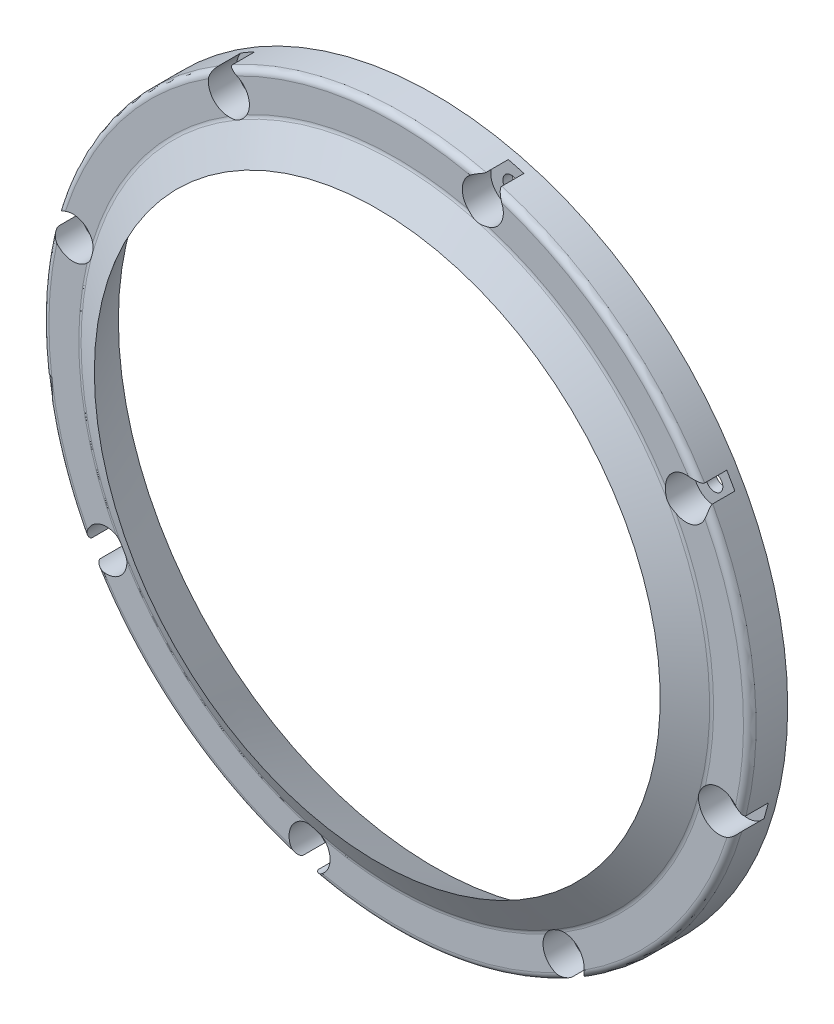
SolidWorks part; units mm, degrees
material "PUR"
ref_plane "Front Plane" through (0, 0, 0) normal (0, 0, 1) x (1, 0, 0)
ref_plane "Top Plane" through (0, 0, 0) normal (0, 1, 0) x (1, 0, 0)
ref_plane "Right Plane" through (0, 0, 0) normal (1, 0, 0) x (0, 0, -1)
sketch "Sketch1" plane through (0, 0, 0) normal (0, 0, 1) x (1, 0, 0)
  circle A0 centre (0, 0) radius 100 construction
  circle A1 centre (0, 0) radius 100
  circle A2 centre (0, 0) radius 112
  arc A3 (111.914, 4.3889) -> (-77.2845, 81.0624) centre (0, 0) ccw construction
sketch "Sketch2" plane through (0, 0, 0) normal (0, 1, 0) x (1, 0, 0)
  line L0 (-112, 0) -> (112, 0) construction
  line L1 (-100, 0) -> (100, 0) construction
  line L2 (-112, 0) -> (112, 0) construction
  line L3 (-100, 0) -> (100, 0) construction
  line L4 (-100, 0) -> (-112, 0)
  line L5 (-100, 0) -> (-89.6077, -18)
  line L6 (0, 0) -> (0, -18) construction
  line L7 (-112, 0) -> (-112, -12)
  line L8 (-89.6077, -18) -> (0, -18) construction
  line L9 (-89.6077, -18) -> (-100, -12)
  line L10 (-100, -12) -> (-112, -12)
  line L11 (-100, -12) -> (-100, 0) construction
  dimension "D1" = 60
  dimension "D2" = 12
  dimension "D3" = 18
revolve "Revolve1" add sketch "Sketch2" angle 360 about L6
fillet "Fillet1" radius 2 2 edges at (-112, 0, 12) (-100, 0, 12)
sketch "Sketch3" plane through (0, 0, 0) normal (0, 0, -1) x (-1, 0, 0)
  circle A0 centre (-102.3881, -27.4348) radius 2.65 construction
  circle A1 centre (-102.3881, -27.4348) radius 2.65
extrude "Cut-Extrude1" cut sketch "Sketch3" against normal through all
sketch "Sketch4" plane through (0, 0, 0) normal (0, 0, -1) x (-1, 0, 0)
  circle A0 centre (-102.3881, -27.4348) radius 6.5
  dimension "D1" = 13
extrude "Cut-Extrude2" cut sketch "Sketch4" against normal through all from offset 3 offset against normal yes
pattern_circular "CirPattern1" count 8 over 360 about axis through (0, 0, 0) along (0, 0, 1) of "Cut-Extrude1", "Cut-Extrude2"
